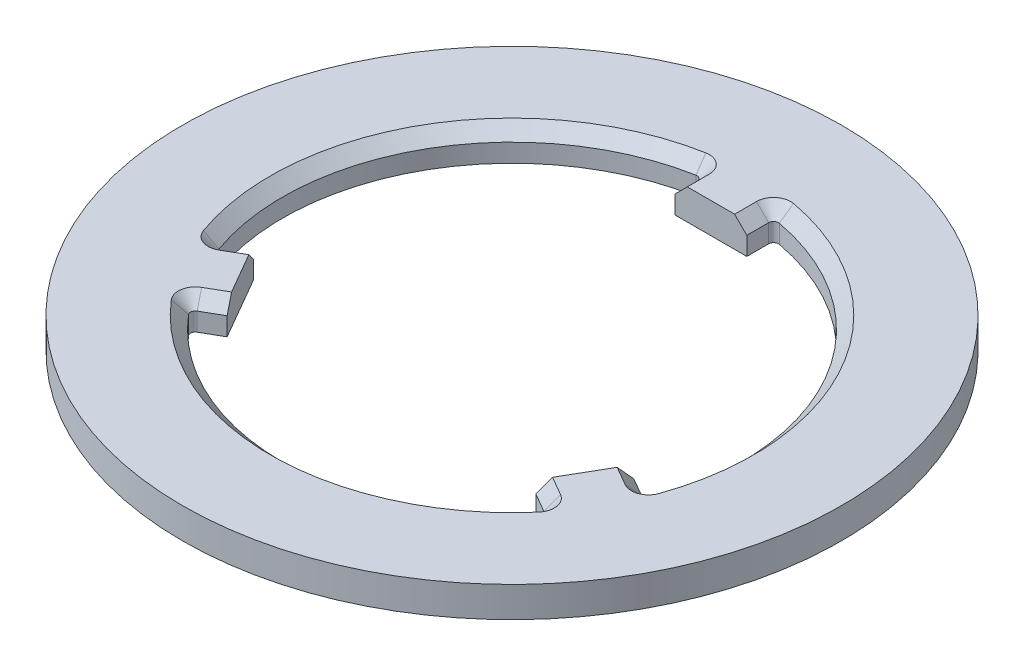
SolidWorks part; units mm, degrees
material "1.0060 (E335)"
ref_plane "Front Plane" through (0, 0, 0) normal (0, 0, 1) x (1, 0, 0)
ref_plane "Top Plane" through (0, 0, 0) normal (0, 1, 0) x (1, 0, 0)
ref_plane "Right Plane" through (0, 0, 0) normal (1, 0, 0) x (0, 0, -1)
sketch "Sketch1" plane through (0, 0, 0) normal (0, 1, 0) x (1, 0, 0)
  circle A0 centre (0, 0) radius 54
  circle A1 centre (0, 0) radius 37.6
  dimension "D1" = 108
  dimension "D2" = 75.2
extrude "Boss-Extrude1" add sketch "Sketch1" along normal mid plane 5
sketch "Sketch2" plane through (0, 0, 0) normal (0, 1, 0) x (1, 0, 0)
  line L0 (0, -1000) -> (0, 49000) construction
  line L1 (-5.875, 32.6) -> (5.875, 32.6)
  line L2 (5.875, 32.6) -> (5.875, 37.1382)
  line L3 (-5.875, 32.6) -> (-5.875, 37.1382)
  circle A0 centre (0, 0) radius 37.6 construction
  arc A1 (5.875, 37.1382) -> (-5.875, 37.1382) centre (0, 0) ccw
  point P5 (0, 32.6)
  dimension "D1" = 11.75
  dimension "D2" = 32.6
extrude "Boss-Extrude2" add sketch "Sketch2" along normal mid plane 5
fillet "Fillet1" radius 0.8 2 edges at (5.875, 0, -37.1382) (-5.875, 0, -37.1382)
pattern_circular "CirPattern1" count 3 over 360 about axis through (0, 0, 0) along (0, 1, 0) of "Boss-Extrude2", "Fillet1"
chamfer "Chamfer2" distance 2 angle 45 15 edges at (5.875, 2.5, -34.3948) (-32.5626, 2.5, -18.8) (-5.875, 2.5, -34.3948) (6.1632, 2.5, -36.8044) (-6.1632, 2.5, -36.8044) (26.8493, 2.5, 22.2853) (-32.7243, 2.5, 12.1095) (32.7243, 2.5, 12.1095) (32.5626, 2.5, -18.8) (28.792, 2.5, 23.7397) (34.9551, 2.5, 13.0647) (-26.8493, 2.5, 22.2853) (0, 2.5, 37.6) (-34.9551, 2.5, 13.0647) (-28.792, 2.5, 23.7397)
